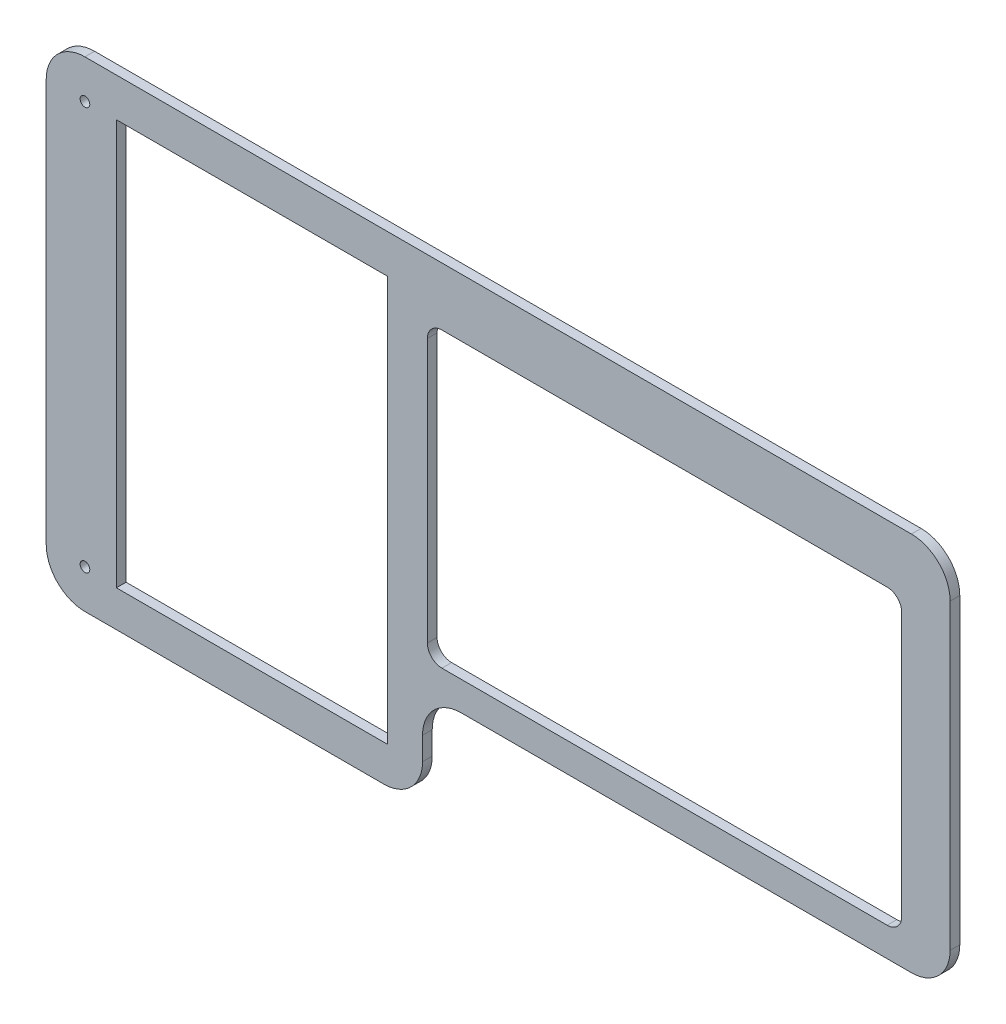
SolidWorks part; units mm, degrees
ref_plane "Front Plane" through (0, 0, 0) normal (0, 0, 1) x (1, 0, 0)
ref_plane "Top Plane" through (0, 0, 0) normal (0, 1, 0) x (1, 0, 0)
ref_plane "Right Plane" through (0, 0, 0) normal (1, 0, 0) x (0, 0, -1)
sketch "Sketch1" plane through (0, 0, 0) normal (0, 0, 1) x (1, 0, 0)
  line L0 (-50, -51.75) -> (-50, -47)
  line L1 (-47, 30) -> (47, 30) construction
  line L2 (-50, 27) -> (-50, -27) construction
  line L3 (-47, -30) -> (47, -30) construction
  line L4 (50, 27) -> (50, -27) construction
  line L5 (-112.75, 31.5) -> (-58, 31.5) construction
  line L6 (-112.75, 31.5) -> (-112.75, -51.75) construction
  line L7 (-112.75, -51.75) -> (-58, -51.75) construction
  line L8 (-58, 31.5) -> (-58, -51.75) construction
  line L9 (-119.75, 39.5) -> (51, 39.5)
  line L10 (-127.75, 31.5) -> (-127.75, -51.75)
  line L11 (-119.75, -59.75) -> (-58, -59.75)
  line L12 (59, 31.5) -> (59, -31)
  line L13 (-42, -39) -> (51, -39)
  arc A0 (51, -39) -> (59, -31) centre (51, -31) ccw
  arc A1 (51, 39.5) -> (59, 31.5) centre (51, 31.5) cw
  arc A2 (-119.75, 39.5) -> (-127.75, 31.5) centre (-119.75, 31.5) ccw
  arc A3 (-127.75, -51.75) -> (-119.75, -59.75) centre (-119.75, -51.75) ccw
  arc A4 (-50, -51.75) -> (-58, -59.75) centre (-58, -51.75) cw
  arc A5 (-50, -47) -> (-42, -39) centre (-42, -47) cw
  arc A6 (47, 30) -> (50, 27) centre (47, 27) cw construction
  arc A7 (47, -30) -> (50, -27) centre (47, -27) ccw construction
  arc A8 (-50, -27) -> (-47, -30) centre (-47, -27) ccw construction
  arc A9 (-47, 30) -> (-50, 27) centre (-47, 27) ccw construction
  point P4 (0, 30)
  point P6 (-50, 0)
  point P31 (50, 30)
  point P36 (-50, -30)
  point P39 (-50, 30)
  dimension "D12" = 8
  dimension "D13" = 3
  dimension "D1" = 100
  dimension "D2" = 60
  dimension "D3" = 54.75
  dimension "D4" = 83.25
  dimension "D5" = 9.5
  dimension "D6" = 8
  dimension "D7" = 9
  dimension "D8" = 15
  dimension "D9" = 8
  dimension "D10" = 8
  dimension "D11" = 9
extrude "Main extrude" add sketch "Sketch1" along normal blind 2
sketch "Sketch2" plane through (0, 0, 2) normal (0, 0, 1) x (1, 0, 0)
  circle A0 centre (-119.75, 31.5) radius 1
  circle A1 centre (-119.75, -51.75) radius 1
  point P44 (52.8891, -32.8891)
  point P45 (52.8891, 33.1391)
  dimension "D1" = 2
extrude "Screwholes" cut sketch "Sketch2" against normal through all both and the other way through all
sketch "Sketch3" plane through (0, 0, 2) normal (0, 0, 1) x (1, 0, 0)
  line L0 (51, 39.5) -> (-119.75, 39.5) construction
  line L1 (-113.25, 31.5) -> (-57.25, 31.5)
  line L2 (-113.25, 31.5) -> (-113.25, -52.25)
  line L3 (-113.25, -52.25) -> (-57.25, -52.25)
  line L4 (-57.25, 31.5) -> (-57.25, -52.25)
  line L5 (-46, 27.5) -> (46, 27.5)
  line L6 (-49, 24.5) -> (-49, -30)
  line L7 (-46, -33) -> (46, -33)
  line L8 (49, 24.5) -> (49, -30)
  line L9 (-127.75, 31.5) -> (-127.75, -51.75) construction
  line L10 (-119.75, -59.75) -> (-58, -59.75) construction
  line L11 (-42, -39) -> (51, -39) construction
  line L12 (59, -31) -> (59, 31.5) construction
  arc A0 (46, 27.5) -> (49, 24.5) centre (46, 24.5) cw
  arc A1 (46, -33) -> (49, -30) centre (46, -30) ccw
  arc A2 (-49, -30) -> (-46, -33) centre (-46, -30) ccw
  arc A3 (-46, 27.5) -> (-49, 24.5) centre (-46, 24.5) ccw
  point P20 (49, 27.5)
  point P27 (-49, 27.5)
  dimension "D9" = 3
  dimension "D1" = 8
  dimension "D2" = 14.5
  dimension "D3" = 7.5
  dimension "D4" = 56
  dimension "D5" = 12
  dimension "D6" = 6
  dimension "D7" = 10
  dimension "D8" = 98
extrude "Cut-Extrude2" cut sketch "Sketch3" against normal through all both and the other way through all
